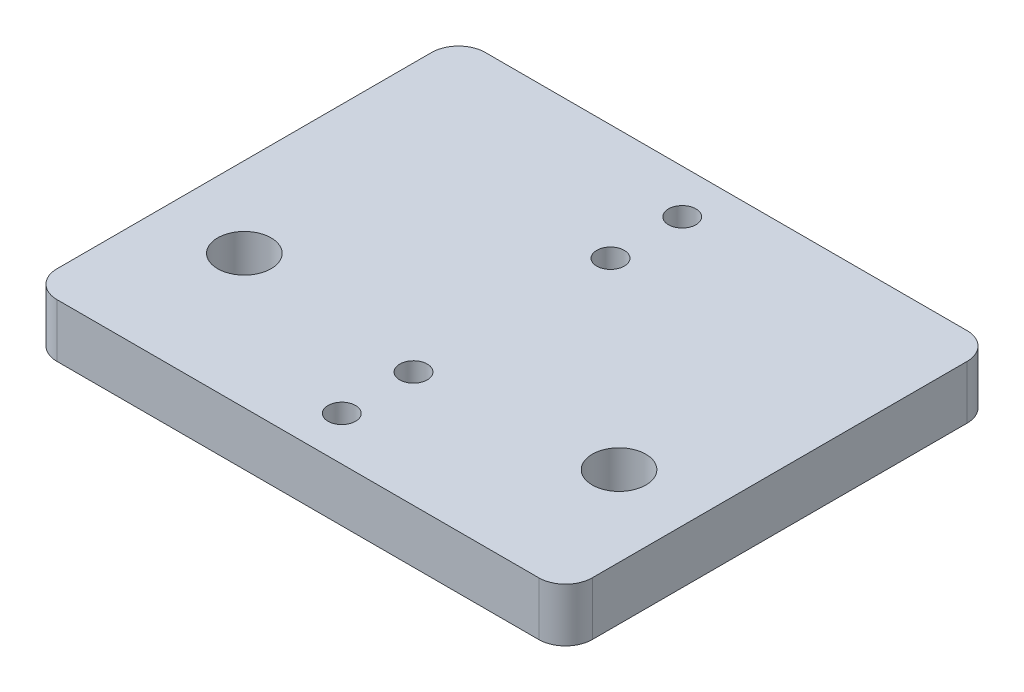
SolidWorks part; units mm, degrees
ref_plane "Front Plane" through (0, 0, 0) normal (0, 0, 1) x (1, 0, 0)
ref_plane "Top Plane" through (0, 0, 0) normal (0, 1, 0) x (1, 0, 0)
ref_plane "Right Plane" through (0, 0, 0) normal (1, 0, 0) x (0, 0, -1)
sketch "Sketch1" plane through (0, 0, 0) normal (0, 1, 0) x (1, 0, 0)
  line L0 (0, 50.8) -> (0, -50.8) construction
  line L1 (-63.5, -6.35) -> (63.5, -6.35) construction
  line L2 (-63.5, -6.35) -> (-63.5, 6.35) construction
  line L3 (-63.5, 6.35) -> (63.5, 6.35) construction
  line L4 (63.5, -6.35) -> (63.5, 6.35) construction
  line L5 (-63.5, -6.35) -> (63.5, 6.35) construction
  line L6 (-63.5, 6.35) -> (63.5, -6.35) construction
  line L7 (-63.5, -50.8) -> (63.5, -50.8)
  line L8 (-63.5, -50.8) -> (-63.5, 50.8)
  line L9 (-63.5, 50.8) -> (63.5, 50.8)
  line L10 (63.5, -50.8) -> (63.5, 50.8)
  line L11 (-63.5, -50.8) -> (63.5, 50.8) construction
  line L12 (-63.5, 50.8) -> (63.5, -50.8) construction
  line L13 (-63.5, 0) -> (63.5, 0) construction
  circle A0 centre (0, 23.368) radius 3.2639
  circle A1 centre (0, 40.386) radius 3.2639
  circle A2 centre (0, -23.368) radius 3.2639
  circle A3 centre (0, -40.386) radius 3.2639
  circle A4 centre (-44.45, -19.05) radius 6.35
  circle A5 centre (44.45, -19.05) radius 6.35
  point P0 (0, 0)
  point P6 (0, 0)
  dimension "D6" = 6.5278
  dimension "D9" = 12.7
  dimension "D1" = 12.7
  dimension "D2" = 127
  dimension "D3" = 44.45
  dimension "D4" = 17.018
  dimension "D5" = 17.018
  dimension "D7" = 127
  dimension "D8" = 88.9
  dimension "D10" = 19.05
  dimension "D11" = 69.85
extrude "Boss-Extrude1" add sketch "Sketch1" along normal mid plane 12.7
fillet "Fillet1" radius 6.35 4 edges at (-63.5, 0, -50.8) (63.5, 0, -50.8) (63.5, 0, 50.8) (-63.5, 0, 50.8)
